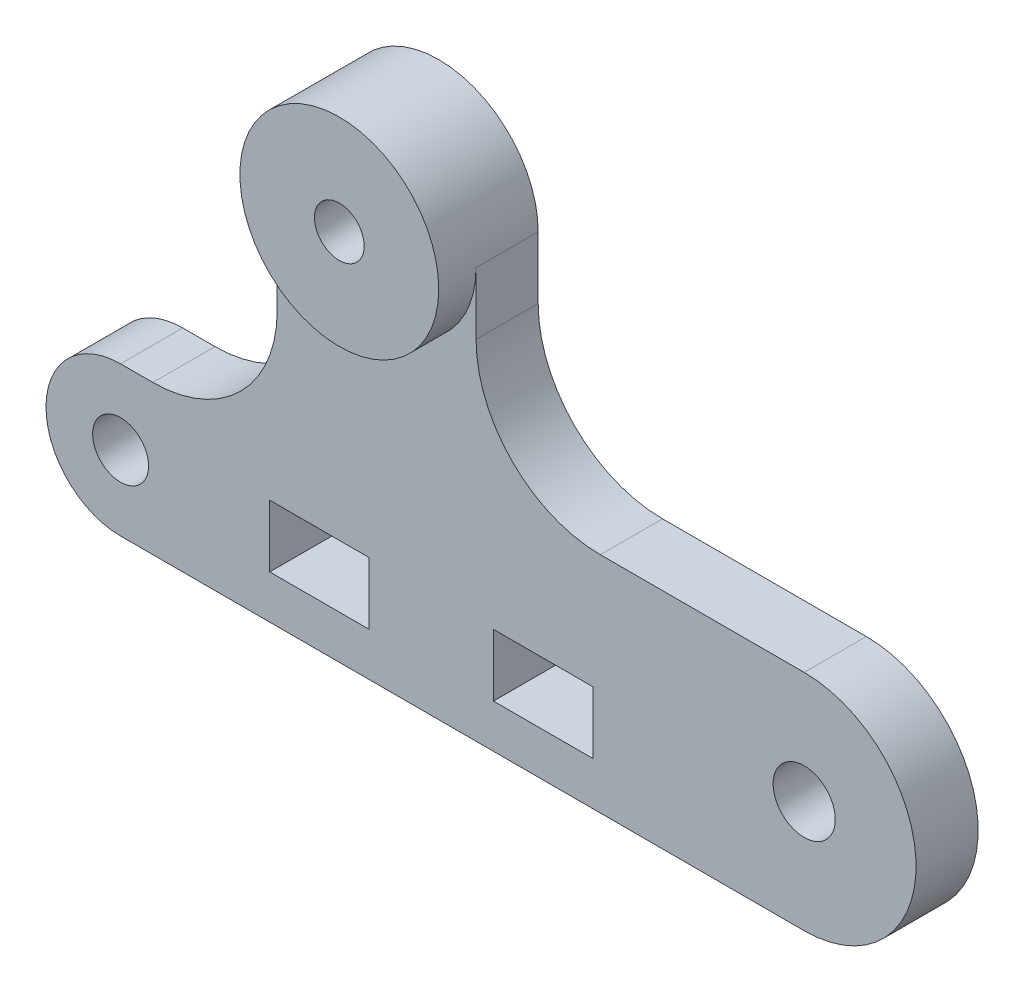
SolidWorks part; units mm, degrees
ref_plane "Ön Düzlem" through (0, 0, 0) normal (0, 0, 1) x (1, 0, 0)
ref_plane "Üst Düzlem" through (0, 0, 0) normal (0, 1, 0) x (1, 0, 0)
ref_plane "Sağ Düzlem" through (0, 0, 0) normal (1, 0, 0) x (0, 0, -1)
sketch "Sketch1" plane through (0, 0, 0) normal (0, 0, 1) x (1, 0, 0)
  line L0 (-27.5, 0) -> (27.5, 0)
  line L1 (-14.9, 33) -> (-14.9, 22)
  line L2 (-24.9, 12) -> (-27.5, 12)
  line L3 (1.1, 33) -> (1.1, 28)
  line L4 (11.1, 18) -> (27.5, 18)
  line L5 (-27.5, 6) -> (-15.5, 6) construction
  line L7 (-15.5, 3.5) -> (-7.5, 3.5)
  line L8 (-15.5, 3.5) -> (-15.5, 8.5)
  line L9 (-15.5, 8.5) -> (-7.5, 8.5)
  line L10 (-7.5, 3.5) -> (-7.5, 8.5)
  line L11 (2.5, 8.5) -> (10.5, 8.5)
  line L12 (2.5, 8.5) -> (2.5, 3.5)
  line L13 (2.5, 3.5) -> (10.5, 3.5)
  line L14 (10.5, 8.5) -> (10.5, 3.5)
  arc A0 (27.5, 0) -> (27.5, 18) centre (27.5, 9) ccw
  arc A1 (-27.5, 0) -> (-27.5, 12) centre (-27.5, 6) cw
  circle A2 centre (27.5, 9) radius 2.5
  circle A3 centre (-27.5, 6) radius 2.25
  circle A4 centre (-6.9, 33) radius 2.25
  circle A5 centre (-6.9, 33) radius 8 construction
  arc A6 (-14.9, 33) -> (1.1, 33) centre (-6.9, 33) cw
  arc A7 (1.1, 28) -> (11.1, 18) centre (11.1, 28) ccw
  arc A8 (-14.9, 22) -> (-24.9, 12) centre (-24.9, 22) cw
  point P3 (0, 0)
  dimension "D2" = 9
  dimension "D3" = 6
  dimension "D4" = 4.5
  dimension "D5" = 5
  dimension "D6" = 33
  dimension "D8" = 16
  dimension "D9" = 10
  dimension "D1" = 55
  dimension "D7" = 6.9
  dimension "D10" = 12
  dimension "D11" = 8
  dimension "D12" = 5
  dimension "D13" = 10
extrude "Boss-Extrude1" add sketch "Sketch1" along normal mid plane 5
sketch "草图2" plane through (0, 0, 2.5) normal (0, 0, 1) x (1, 0, 0)
  circle A0 centre (-6.9, 33) radius 8
  circle A1 centre (-6.9, 33) radius 2
extrude "凸台-拉伸1" add sketch "草图2" along normal blind 3
